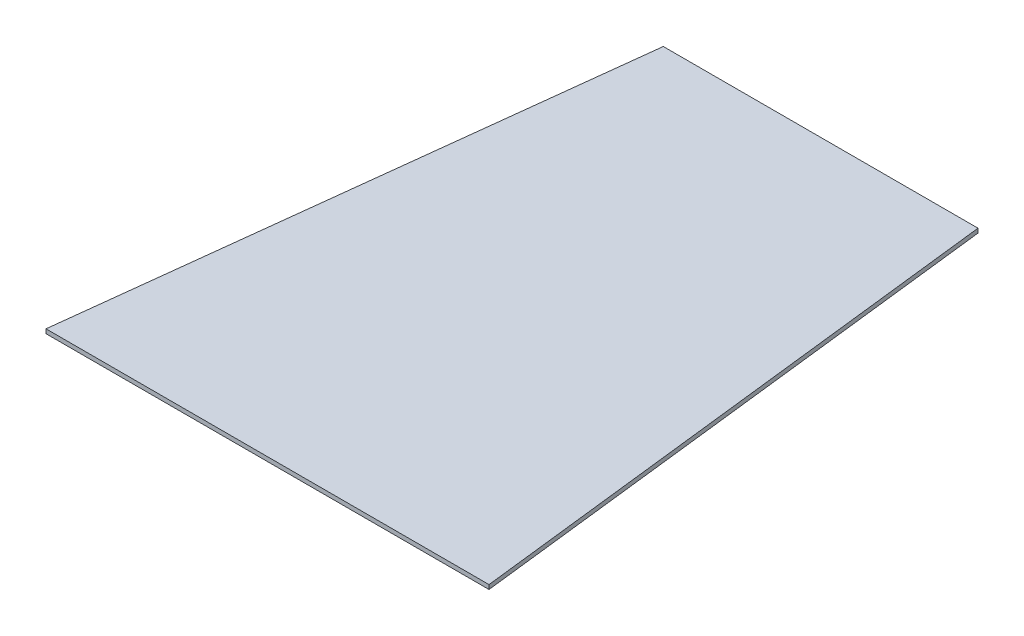
SolidWorks part; units mm, degrees
ref_plane "Front Plane" through (0, 0, 0) normal (0, 0, 1) x (1, 0, 0)
ref_plane "Top Plane" through (0, 0, 0) normal (0, 1, 0) x (1, 0, 0)
ref_plane "Right Plane" through (0, 0, 0) normal (1, 0, 0) x (0, 0, -1)
sketch "Sketch1" plane through (0, 0, 0) normal (0, 1, 0) x (1, 0, 0)
  line L1 (0, 0) -> (500, 0)
  line L2 (0, 0) -> (0, -500)
  line L3 (0, -500) -> (500, -500)
  line L4 (500, 0) -> (500, -500)
extrude "Boss-Extrude1" add sketch "Sketch1" along normal blind 2.9972
sketch "Sketch3" plane through (0, 0, 0) normal (0, -1, 0) x (1, 0, 0)
  line L0 (168.791, 0) -> (123.6727, 388.9543)
  line L1 (123.6727, 388.9543) -> (435.1924, 388.9543)
  line L2 (435.1924, 388.9543) -> (390.0741, 0)
  line L3 (500, 0) -> (0, 0) construction
  line L4 (435.1924, 388.9543) -> (390.0741, 0) construction
  line L5 (390.0741, 0) -> (168.791, 0)
extrude "Cut-Extrude1" cut sketch "Sketch3" against normal through all flip side to cut
